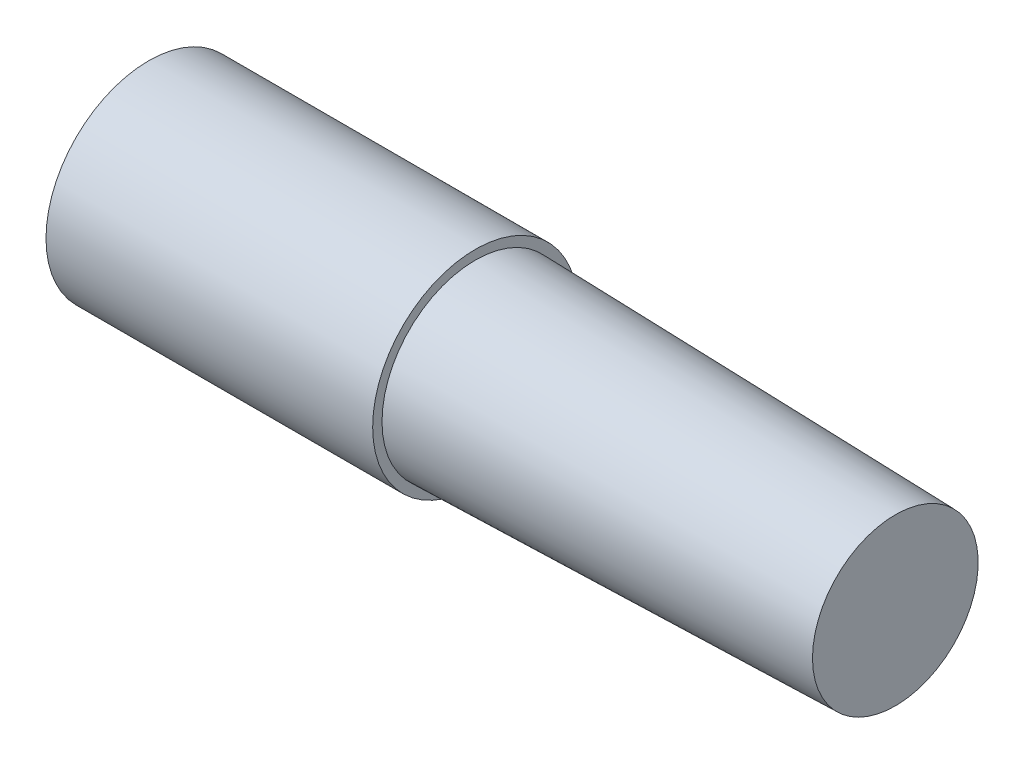
SolidWorks part; units mm, degrees
ref_plane "Front Plane" through (0, 0, 0) normal (0, 0, 1) x (1, 0, 0)
ref_plane "Top Plane" through (0, 0, 0) normal (0, 1, 0) x (1, 0, 0)
ref_plane "Right Plane" through (0, 0, 0) normal (1, 0, 0) x (0, 0, -1)
sketch "Sketch1" plane through (0, 0, 0) normal (0, 0, 1) x (1, 0, 0)
  line L0 (0, 0) -> (80, 0) construction
  line L1 (0, 0) -> (0, 11) construction
  line L2 (0, 11) -> (35, 11)
  line L3 (35, 11) -> (35, 10)
  line L4 (35, 10) -> (80, 8.875)
  line L5 (80, 8.875) -> (80, 0)
  line L6 (0, 11) -> (-6.3509, 0)
  line L7 (-6.3509, 0) -> (0, 0)
  line L8 (0, 0) -> (80, 0)
  dimension "D1" = 80
  dimension "D2" = 11
  dimension "D3" = 20
  dimension "D4" = 45
  dimension "D5" = 30
  dimension "D6" = 17.75
revolve "Revolve1" add sketch "Sketch1" angle 360 about L8
